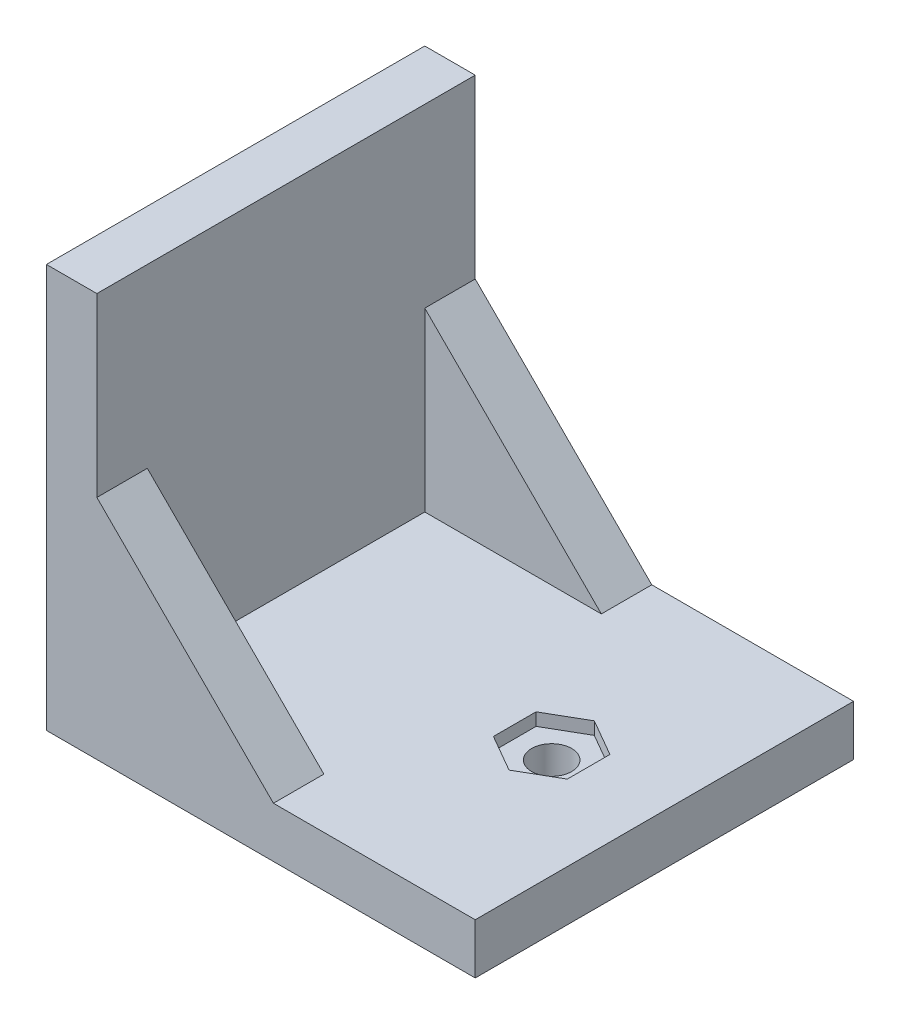
SolidWorks part; units mm, degrees
material "ABS"
ref_plane "Front Plane" through (0, 0, 0) normal (0, 0, 1) x (1, 0, 0)
ref_plane "Top Plane" through (0, 0, 0) normal (0, 1, 0) x (1, 0, 0)
ref_plane "Right Plane" through (0, 0, 0) normal (1, 0, 0) x (0, 0, -1)
sketch "Sketch1" plane through (0, 0, 0) normal (0, 1, 0) x (1, 0, 0)
  line L1 (0, 0) -> (68, 0)
  line L2 (0, 0) -> (0, 60)
  line L3 (0, 60) -> (68, 60)
  line L4 (68, 0) -> (68, 60)
  dimension "D1" = 68
  dimension "D2" = 60
extrude "Boss-Extrude1" add sketch "Sketch1" along normal blind 8
sketch "Sketch4" plane through (0, 8, 0) normal (0, 1, 0) x (1, 0, 0)
  line L0 (8, 0) -> (8, 60)
  line L1 (0, 0) -> (68, 0) construction
  line L2 (68, 60) -> (0, 60) construction
  line L3 (0, 60) -> (0, 0) construction
  line L4 (0, 0) -> (8, 0)
  line L5 (0, 60) -> (0, 0)
  line L6 (8, 60) -> (0, 60)
  dimension "D1" = 8
extrude "Boss-Extrude2" add sketch "Sketch4" along normal blind 56
sketch "Sketch5" plane through (0, 8, 0) normal (0, 1, 0) x (1, 0, 0)
  line L1 (8, 0) -> (68, 0) construction
  line L3 (68, 0) -> (68, 60) construction
  circle A0 centre (50.125, 30) radius 3.175
  dimension "D1" = 6.35
  dimension "D2" = 30
  dimension "D3" = 17.875
extrude "Cut-Extrude1" cut sketch "Sketch5" against normal blind 8
sketch "Sketch7" plane through (0, 8, 0) normal (0, 1, 0) x (1, 0, 0)
  line L20 (44.2688, 26.6189) -> (50.125, 23.2378)
  line L21 (50.125, 23.2378) -> (55.9813, 26.6189)
  line L22 (55.9813, 26.6189) -> (55.9813, 33.3811)
  line L23 (55.9813, 33.3811) -> (50.125, 36.7622)
  line L24 (50.125, 36.7622) -> (44.2688, 33.3811)
  line L25 (44.2688, 33.3811) -> (44.2688, 26.6189)
  line L26 (55.6812, 33.2079) -> (50.125, 36.4158) construction
  line L27 (50.125, 36.4158) -> (44.5688, 33.2079) construction
  line L28 (44.5688, 33.2079) -> (44.5688, 26.7921) construction
  line L29 (44.5688, 26.7921) -> (50.125, 23.5842) construction
  line L30 (50.125, 23.5842) -> (55.6812, 26.7921) construction
  line L31 (55.6812, 26.7921) -> (55.6812, 33.2079) construction
  dimension "D2" = 0.3
  dimension "D3" = 0.3
  dimension "D4" = 0.3
  dimension "D5" = 0.3
  dimension "D6" = 0.3
  dimension "D7" = 0.3
extrude "Cut-Extrude2" cut sketch "Sketch7" against normal blind 2
sketch "Sketch8" plane through (0, 0, -60) normal (0, 0, -1) x (-1, 0, 0)
  line L0 (-68, 8) -> (-8, 8) construction
  line L1 (-8, 64) -> (-8, 8) construction
  line L2 (-36, 8) -> (-8, 8)
  line L3 (-8, 36) -> (-8, 8)
  line L4 (-36, 8) -> (-8, 36)
  dimension "D1" = 45
  dimension "D2" = 28
extrude "Boss-Extrude3" add sketch "Sketch8" against normal blind 8
ref_plane "Plane1" through (0, 0, -30) normal (0, 0, -1) x (-1, 0, 0)
mirror "Mirror1" about plane through (0, 0, -30) normal (0, 0, -1) of "Boss-Extrude3"
